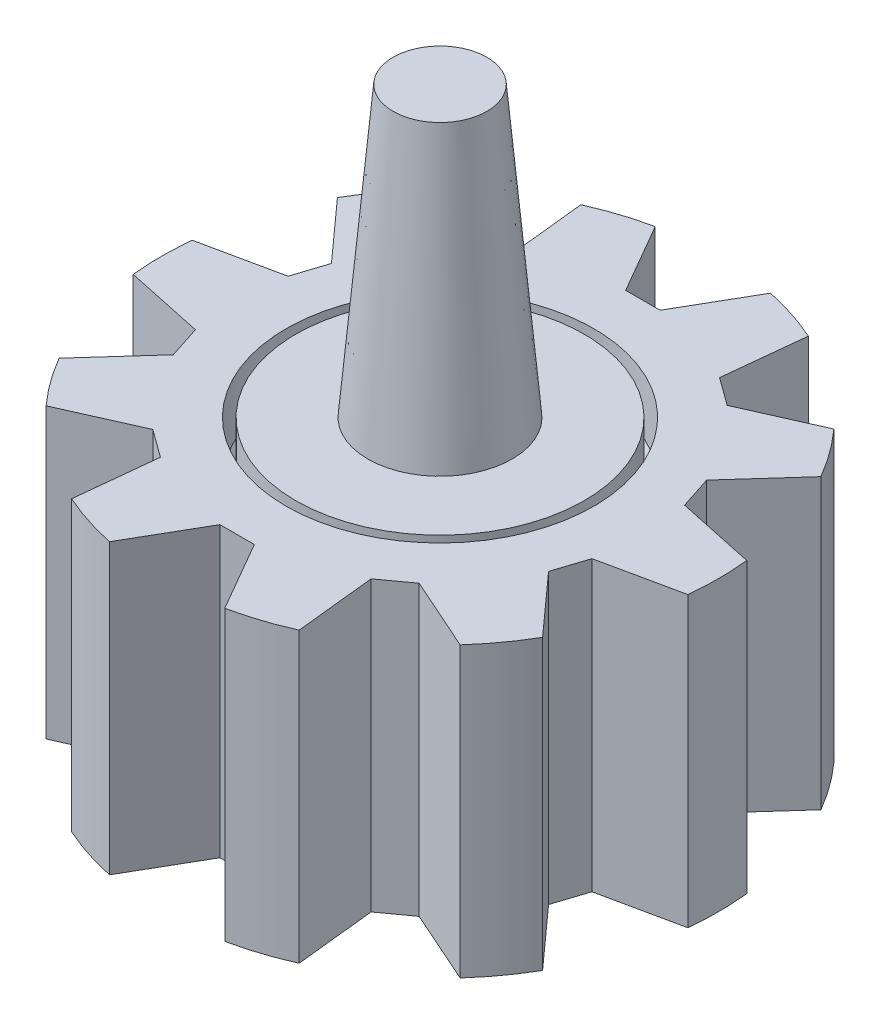
SolidWorks part; units mm, degrees
ref_plane "Front Plane" through (0, 0, 0) normal (0, 0, 1) x (1, 0, 0)
ref_plane "Top Plane" through (0, 0, 0) normal (0, 1, 0) x (1, 0, 0)
ref_plane "Right Plane" through (0, 0, 0) normal (1, 0, 0) x (0, 0, -1)
sketch "Sketch1" plane through (0, 0, 0) normal (0, 0, 1) x (1, 0, 0)
  line L1 (0, 67.5789) -> (0, -59.5789) construction
  line L2 (15, 30) -> (15, 25)
  line L3 (15, 25) -> (10, 20)
  line L4 (10, 20) -> (10, 10)
  line L5 (10, 10) -> (15, 5)
  line L6 (15, 5) -> (15, 0)
  line L7 (15, 0) -> (0, 0)
  line L8 (15, 30) -> (0, 30)
  line L9 (0, 0) -> (0, 30)
  dimension "D1" = 15
  dimension "D2" = 5
  dimension "D3" = 135
  dimension "D4" = 5
  dimension "D5" = 10
revolve "Revolve1" add sketch "Sketch1" angle 360 about L1
sketch "Sketch2" plane through (0, 0, 0) normal (0, 0, 1) x (1, 0, 0)
  line L1 (0, 82.9855) -> (0, -61.1228) construction
  line L8 (10, 10) -> (10, 20) construction
  line L9 (10, 10) -> (10, 20) construction
  line L18 (16, 30) -> (29, 30)
  line L19 (29, 30) -> (29, 0)
  line L20 (29, 0) -> (16, 0)
  line L23 (16, 0) -> (16, 5.8284)
  line L24 (16, 5.8284) -> (11, 10.8284)
  line L25 (11, 10.8284) -> (11, 19.1716)
  line L26 (11, 19.1716) -> (16, 24.1716)
  line L27 (16, 24.1716) -> (16, 30)
  dimension "D1" = 1
  dimension "D2" = 13
revolve "Revolve2" add sketch "Sketch2" angle 360 about L1
sketch "Sketch8" plane through (0, 0, 0) normal (0, -1, 0) x (1, 0, 0)
  line L4 (-1.7904, -21.0952) -> (1.7904, -21.0952)
  line L5 (-1.7904, -21.0952) -> (-10.8172, -36.73)
  line L6 (-10.8172, -36.73) -> (10.8172, -36.73)
  line L7 (10.8172, -36.73) -> (1.7904, -21.0952)
  point P3 (6.803, -24.1391)
  point P5 (-3.5053, -24.0655)
  point P6 (0, -21.0952)
  dimension "D1" = 120
  dimension "D2" = 120
sketch "Sketch4" plane through (0, 30, 0) normal (0, 1, 0) x (1, 0, 0)
  circle A0 centre (0, 0) radius 7.5
  dimension "D1" = 15
extrude "Cut-Extrude1" cut sketch "Sketch8" against normal through all contours L6 L7 L4 L5
pattern_circular "CirPattern1" count 10 over 360 about axis through (0, 0, 0) along (0, 1, 0) of "Cut-Extrude1"
extrude "Boss-Extrude1" add sketch "Sketch4" along normal blind 30 draft 5
